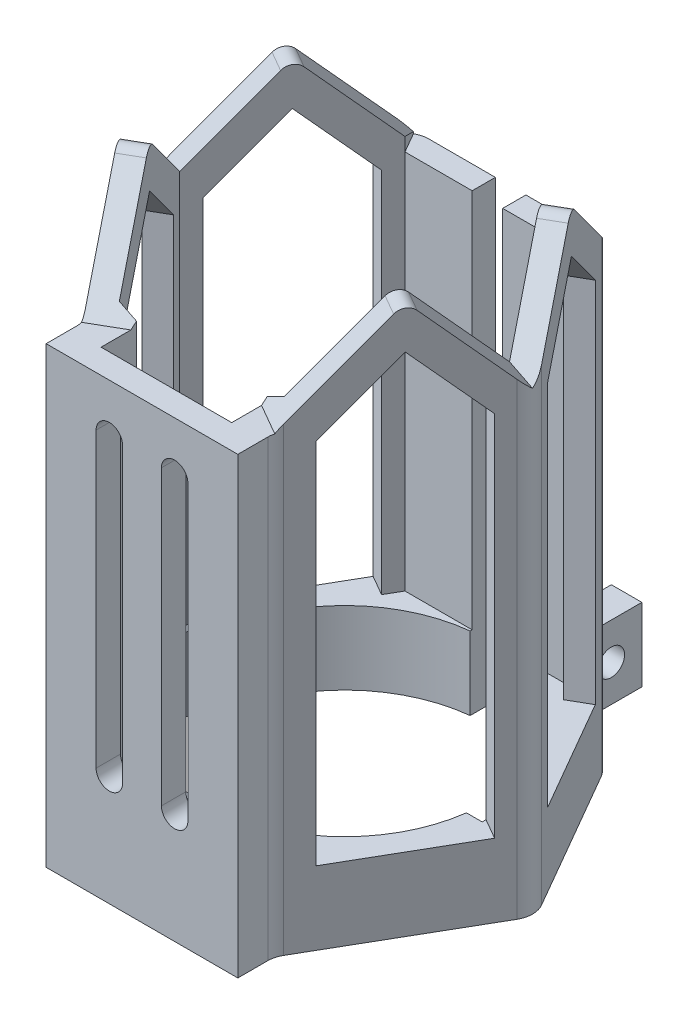
SolidWorks part; units mm, degrees
ref_plane "Front Plane" through (0, 0, 0) normal (0, 0, 1) x (1, 0, 0)
ref_plane "Top Plane" through (0, 0, 0) normal (0, 1, 0) x (1, 0, 0)
ref_plane "Right Plane" through (0, 0, 0) normal (1, 0, 0) x (0, 0, -1)
sketch "Sketch1" plane through (0, 0, 0) normal (0, 1, 0) x (1, 0, 0)
  line L1 (39.8834, 0) -> (19.9417, 34.54)
  line L2 (19.9417, 34.54) -> (9.525, 34.54)
  line L3 (-19.9417, 34.54) -> (-39.8834, 0)
  line L4 (-39.8834, 0) -> (-19.9417, -34.54)
  line L5 (-19.9417, -34.54) -> (19.9417, -34.54)
  line L6 (19.9417, -34.54) -> (39.8834, 0)
  line L7 (0, -55) -> (0, 55) construction
  line L8 (-3.175, 34.54) -> (-3.175, 52.32)
  line L9 (-3.175, 52.32) -> (-9.525, 52.32)
  line L10 (-9.525, 52.32) -> (-9.525, 34.54)
  line L11 (3.175, 52.32) -> (9.525, 52.32)
  line L12 (9.525, 52.32) -> (9.525, 34.54)
  line L13 (3.175, 34.54) -> (3.175, 52.32)
  line L14 (-3.175, 34.54) -> (-3.175, 29.2884)
  line L15 (3.175, 34.54) -> (3.175, 29.2884)
  line L17 (-9.525, 34.54) -> (-19.9417, 34.54)
  arc A0 (-3.175, 29.2884) -> (3.175, 29.2884) centre (0, 0) ccw
  circle A1 centre (0, 0) radius 34.54 construction
  dimension "D1" = 58.92
  dimension "D3" = 5.08
  dimension "D4" = 6.35
  dimension "D5" = 6.35
  dimension "D6" = 17.78
extrude "Boss-Extrude1" add sketch "Sketch1" along normal blind 114.3
sketch "Sketch2" plane through (0, 114.3, 0) normal (0, 1, 0) x (1, 0, 0)
  line L0 (0, -55) -> (0, 55) construction
  line L1 (-9.525, 34.54) -> (-3.175, 34.54)
  line L2 (-9.525, 34.54) -> (-9.525, 52.32)
  line L3 (-9.525, 52.32) -> (-3.175, 52.32)
  line L4 (-3.175, 34.54) -> (-3.175, 52.32)
  line L5 (9.525, 52.32) -> (3.175, 52.32)
  line L6 (3.175, 34.54) -> (3.175, 52.32)
  line L7 (9.525, 34.54) -> (3.175, 34.54)
  line L8 (9.525, 34.54) -> (9.525, 52.32)
extrude "Cut-Extrude2" cut sketch "Sketch2" against normal blind 99.06
sketch "Sketch3" plane through (-29.9125, 0, -17.27) normal (-0.866, 0, -0.5) x (-0.5, 0, 0.866)
  line L0 (-19.9417, 57.15) -> (19.9417, 57.15) construction
  line L1 (-19.9417, 114.3) -> (-19.9417, 0) construction
  line L2 (19.9417, 114.3) -> (19.9417, 0) construction
  line L3 (-19.9417, 114.3) -> (19.9417, 114.3) construction
  line L4 (-13.5917, 15.24) -> (13.5917, 15.24)
  line L5 (-13.5917, 15.24) -> (-13.5917, 99.06)
  line L6 (-13.5917, 99.06) -> (13.5917, 99.06)
  line L7 (13.5917, 15.24) -> (13.5917, 99.06)
  line L10 (-13.5917, 15.24) -> (13.5917, 99.06) construction
  line L16 (-13.5917, 99.06) -> (13.5917, 15.24) construction
  point P6 (0, 57.15)
  dimension "D1" = 15.24
  dimension "D2" = 6.35
extrude "Cut-Extrude3" cut sketch "Sketch3" against normal blind 99.06
sketch "Sketch4" plane through (29.9125, 0, -17.27) normal (0.866, 0, -0.5) x (-0.5, 0, -0.866)
  line L4 (-19.9417, 57.15) -> (19.9417, 57.15) construction
  line L5 (-19.9417, 114.3) -> (-19.9417, 0) construction
  line L6 (19.9417, 114.3) -> (19.9417, 0) construction
  line L7 (-19.9417, 114.3) -> (19.9417, 114.3) construction
  line L8 (-13.5917, 15.24) -> (13.5917, 15.24)
  line L9 (-13.5917, 15.24) -> (-13.5917, 99.06)
  line L10 (-13.5917, 99.06) -> (13.5917, 99.06)
  line L11 (13.5917, 15.24) -> (13.5917, 99.06)
  line L16 (-13.5917, 15.24) -> (13.5917, 99.06) construction
  line L17 (-13.5917, 99.06) -> (13.5917, 15.24) construction
  point P6 (0, 57.15)
  dimension "D1" = 15.24
  dimension "D2" = 6.35
extrude "Cut-Extrude4" cut sketch "Sketch4" against normal blind 99.06
sketch "Sketch7" plane through (0, 0, 0) normal (0, -1, 0) x (1, 0, 0)
  line L0 (43.8717, 0) -> (-43.8717, 0) construction
  line L1 (-32.47, -3.8568) -> (-29.2064, -3.8568)
  line L2 (-32.47, -3.8568) -> (-32.47, 3.8568)
  line L3 (-32.47, 3.8568) -> (-29.2064, 3.8568)
  line L4 (-29.2064, -3.8568) -> (-29.2064, 3.8568)
  line L5 (-32.47, -3.8568) -> (-29.2064, 3.8568) construction
  line L6 (-32.47, 3.8568) -> (-29.2064, -3.8568) construction
  line L7 (0, -65.4668) -> (0, 65.4668) construction
  line L8 (32.47, 3.8568) -> (29.2064, 3.8568)
  line L9 (29.2064, -3.8568) -> (29.2064, 3.8568)
  line L10 (32.47, -3.8568) -> (29.2064, -3.8568)
  line L11 (32.47, -3.8568) -> (32.47, 3.8568)
  arc A0 (3.175, -29.2884) -> (-3.175, -29.2884) centre (0, 0) ccw construction
  point P0 (-30.8382, 0)
  dimension "D1" = 3.2635
  dimension "D2" = 7.7136
extrude "Cut-Extrude7" cut sketch "Sketch7" against normal blind 15.24
sketch "Sketch8" plane through (0, 114.3, 0) normal (0, 1, 0) x (1, 0, 0)
  line L28 (-3.175, 29.714) -> (3.175, 29.714)
  line L35 (-34.3108, 0) -> (-17.1554, -29.714)
  line L36 (-17.1554, -29.714) -> (17.1554, -29.714)
  line L37 (17.1554, -29.714) -> (34.3108, 0)
  line L38 (34.3108, 0) -> (17.1554, 29.714)
  line L39 (17.1554, 29.714) -> (3.175, 29.714)
  line L40 (-17.1554, 29.714) -> (-34.3108, 0)
  line L41 (-3.175, 29.714) -> (-17.1554, 29.714)
  line L42 (-34.3108, 0) -> (-17.1554, -29.714)
  line L43 (-17.1554, -29.714) -> (17.1554, -29.714)
  line L44 (17.1554, -29.714) -> (34.3108, 0)
  line L45 (34.3108, 0) -> (17.1554, 29.714)
  line L46 (17.1554, 29.714) -> (3.175, 29.714)
  line L47 (-17.1554, 29.714) -> (-34.3108, 0)
  line L48 (-3.175, 29.714) -> (-17.1554, 29.714)
  dimension "D1" = 4.826
extrude "Cut-Extrude8" cut sketch "Sketch8" against normal blind 99.06
sketch "Sketch10" plane through (0, 0, 34.54) normal (0, 0, 1) x (1, 0, 0)
  line L0 (43.8717, 0) -> (-43.8717, 0) construction
  line L1 (-19.9417, 114.3) -> (19.9417, 114.3)
  line L2 (-19.9417, 114.3) -> (-19.9417, 0)
  line L3 (-19.9417, 0) -> (19.9417, 0)
  line L4 (19.9417, 114.3) -> (19.9417, 0)
  line L5 (19.9417, 114.3) -> (19.9417, 0) construction
extrude "Boss-Extrude2" add sketch "Sketch10" along normal blind 7.62
sketch "Sketch11" plane through (-29.9125, 0, -17.27) normal (-0.866, 0, -0.5) x (-0.5, 0, 0.866)
  line L0 (-13.5917, 91.7281) -> (0, 105.3197)
  line L1 (0, 0) -> (0, 114.3) construction
  line L2 (-19.9417, 94.3583) -> (0, 114.3)
  line L3 (-19.9417, 114.3) -> (-19.9417, 0) construction
  line L4 (-19.9417, 114.3) -> (19.9417, 114.3) construction
  line L7 (-13.5917, 99.06) -> (-13.5917, 15.24) construction
  line L8 (-13.5917, 91.7281) -> (0, 91.7281) construction
  line L9 (19.9417, 94.3583) -> (0, 114.3)
  line L10 (13.5917, 91.7281) -> (0, 105.3197)
  line L11 (-19.9417, 94.3583) -> (-13.5917, 91.7281)
  line L12 (13.5917, 91.7281) -> (19.9417, 94.3583)
  dimension "D1" = 6.35
  dimension "D2" = 45
sketch "Sketch12" plane through (-29.9125, 0, -17.27) normal (-0.866, 0, -0.5) x (-0.5, 0, 0.866)
  line L0 (0, 114.3) -> (-19.9417, 94.3583)
  line L1 (-19.9417, 94.3583) -> (-19.9417, 114.3)
  line L2 (-19.9417, 114.3) -> (0, 114.3)
  line L3 (0, 114.3) -> (19.9417, 114.3)
  line L4 (19.9417, 114.3) -> (19.9417, 94.3583)
  line L5 (19.9417, 94.3583) -> (0, 114.3)
  line L6 (0, 105.3197) -> (-6.2597, 99.06)
  line L7 (13.5917, 99.06) -> (-13.5917, 99.06) construction
  line L8 (-6.2597, 99.06) -> (6.2597, 99.06)
  line L9 (6.2597, 99.06) -> (0, 105.3197)
  line L10 (13.5917, 91.7281) -> (0, 105.3197) construction
  line M4 (-13.5917, 99.06) -> (13.5917, 99.06)
  line M9 (19.9417, 0) -> (19.9417, 114.3)
  line M10 (19.9417, 114.3) -> (-19.9417, 114.3)
  line M11 (-19.9417, 114.3) -> (-19.9417, 0)
extrude "Cut-Extrude11" cut sketch "Sketch12" against normal blind 81.28 contours L5 M9 M10 | L0 M10 M11 | L9 L6 M4
mirror "Mirror2" about plane through (0, 0, 0) normal (1, 0, 0) of "Cut-Extrude11"
sketch "Sketch14" plane through (0, 0, -34.54) normal (0, 0, -1) x (-1, 0, 0)
  line L0 (-19.9417, 94.3583) -> (19.9417, 94.3583)
  line L1 (19.9417, 94.3583) -> (19.9417, 114.3)
  line L2 (19.9417, 114.3) -> (-19.9417, 114.3)
  line L3 (-19.9417, 114.3) -> (-19.9417, 94.3583)
extrude "Boss-Extrude9" add sketch "Sketch11" against normal blind 4.826
mirror "Mirror8" about plane through (0, 0, 0) normal (0, 0, 1) of "Boss-Extrude9"
mirror "Mirror9" about plane through (0, 0, 0) normal (1, 0, 0) of "Mirror8"
sketch "Sketch15" plane through (0, 114.3, 0) normal (0, 1, 0) x (1, 0, 0)
  line L0 (-17.1554, 29.714) -> (-19.9417, 34.54)
  line L1 (-19.9417, 34.54) -> (19.9417, 34.54)
  line L2 (19.9417, 34.54) -> (17.1554, 29.714)
  line L3 (17.1554, 29.714) -> (-17.1554, 29.714)
extrude "Cut-Extrude13" cut sketch "Sketch15" against normal blind 19.9417
sketch "Sketch16" plane through (0, 114.3, 0) normal (0, 1, 0) x (1, 0, 0)
  line L0 (-19.9417, -34.54) -> (19.9417, -34.54)
  line L1 (19.9417, -34.54) -> (11.5828, -29.714)
  line L2 (11.5828, -29.714) -> (-11.5828, -29.714)
  line L3 (-11.5828, -29.714) -> (-19.9417, -34.54)
extrude "Cut-Extrude14" cut sketch "Sketch16" against normal blind 19.9417
sketch "Sketch17" plane through (0, 114.3, 0) normal (0, 1, 0) x (1, 0, 0)
  line L0 (0, -29.714) -> (0, -34.54) construction
  line L1 (11.5828, -29.714) -> (-11.5828, -29.714) construction
  line L2 (0, -47.773) -> (0, 47.773) construction
  line L3 (-19.9417, -34.54) -> (19.9417, -34.54) construction
  line L4 (-17.1554, -29.714) -> (17.1554, -29.714) construction
  line L5 (-13.5917, -34.54) -> (13.5917, -34.54)
  line L6 (-13.5917, -34.54) -> (-13.5917, -29.714)
  line L7 (-13.5917, -29.714) -> (13.5917, -29.714)
  line L8 (13.5917, -34.54) -> (13.5917, -29.714)
  line L9 (-13.5917, -34.54) -> (13.5917, -29.714) construction
  line L10 (-13.5917, -29.714) -> (13.5917, -34.54) construction
  point P10 (0, -32.127)
  dimension "D1" = 3.5637
extrude "Cut-Extrude15" cut sketch "Sketch17" against normal blind 99.06
sketch "Sketch18" plane through (0, 114.3, 0) normal (0, 1, 0) x (1, 0, 0)
  line L0 (19.9417, -34.54) -> (13.5917, -30.8738) construction
  line L1 (-19.9417, -42.16) -> (19.9417, -42.16)
  line L2 (-19.9417, -42.16) -> (-19.9417, -34.54)
  line L3 (-19.9417, -34.54) -> (19.9417, -34.54)
  line L4 (19.9417, -42.16) -> (19.9417, -34.54)
  line L5 (13.5917, -34.54) -> (19.9417, -34.54) construction
extrude "Cut-Extrude16" cut sketch "Sketch18" against normal blind 19.9417
sketch "Sketch19" plane through (0, 0, 42.16) normal (0, 0, 1) x (1, 0, 0)
  line L0 (-6.7958, 23.07) -> (-6.7958, 83.9883) construction
  line L1 (-9.5458, 23.07) -> (-9.5458, 83.9883)
  line L2 (-4.0458, 23.07) -> (-4.0458, 83.9883)
  line L3 (43.8717, 0) -> (-43.8717, 0) construction
  line L4 (-4.0458, 53.5292) -> (0, 53.5292) construction
  line L6 (-9.5458, 53.5292) -> (-13.5917, 53.5292) construction
  line L7 (0, -51.964) -> (0, 51.964) construction
  line L8 (-6.7958, 86.7383) -> (-6.7958, 94.3583) construction
  line L9 (-19.9417, 94.3583) -> (19.9417, 94.3583) construction
  line L10 (6.7958, 23.07) -> (6.7958, 83.9883) construction
  line L11 (9.5458, 23.07) -> (9.5458, 83.9883)
  line L12 (4.0458, 23.07) -> (4.0458, 83.9883)
  line L13 (-13.5917, 15.24) -> (-13.5917, 94.3583) construction
  arc A0 (-9.5458, 23.07) -> (-4.0458, 23.07) centre (-6.7958, 23.07) ccw
  arc A1 (-4.0458, 83.9883) -> (-9.5458, 83.9883) centre (-6.7958, 83.9883) ccw
  arc A2 (9.5458, 23.07) -> (4.0458, 23.07) centre (6.7958, 23.07) cw
  arc A3 (4.0458, 83.9883) -> (9.5458, 83.9883) centre (6.7958, 83.9883) cw
  point P2 (-6.7958, 53.5292)
  point P7 (-6.7958, 20.32)
  point P24 (6.7958, 53.5292)
  dimension "D1" = 20.32
  dimension "D2" = 5.5
  dimension "D3" = 7.62
extrude "Cut-Extrude18" cut sketch "Sketch19" against normal blind 19.9417
sketch "Sketch20" plane through (0, 94.3583, 0) normal (0, 1, 0) x (1, 0, 0)
  line L0 (-13.5917, -34.54) -> (-13.5917, -37.08)
  line L1 (-13.5917, -37.08) -> (13.5917, -37.08)
  line L2 (13.5917, -34.54) -> (13.5917, -37.08)
  line L3 (-13.5917, -34.54) -> (13.5917, -34.54)
  line L4 (-19.9417, -42.16) -> (19.9417, -42.16) construction
  dimension "D1" = 5.08
extrude "Cut-Extrude19" cut sketch "Sketch20" against normal blind 79.1183
fillet "Fillet1" radius 5.08 8 edges at (19.9417, 47.1792, 34.54) (-19.9417, 47.1792, 34.54) (39.8834, 47.1792, 0) (19.9417, 47.1792, -34.54) (9.525, 7.62, -34.54) (-9.525, 7.62, -34.54) (-39.8834, 47.1792, 0) (-19.9417, 47.1792, -34.54)
fillet "Fillet2" radius 2.54 4 edges at (27.8228, 114.3, 16.0635) (-27.8228, 114.3, -16.0635) (-27.8228, 114.3, 16.0635) (27.8228, 114.3, -16.0635)
sketch "Sketch21" plane through (9.525, 0, 0) normal (1, 0, 0) x (0, 0, -1)
  line L0 (45.97, 15.24) -> (45.97, 0) construction
  line L1 (39.62, 15.24) -> (52.32, 15.24) construction
  line L2 (43.0072, 0) -> (-43.0072, 0) construction
  circle A0 centre (45.97, 7.62) radius 2.75
  circle A1 centre (45.97, 7.62) radius 4.75 construction
  dimension "D1" = 5.5
  dimension "D2" = 9.5
extrude "Cut-Extrude20" cut sketch "Sketch21" against normal blind 79.1183
